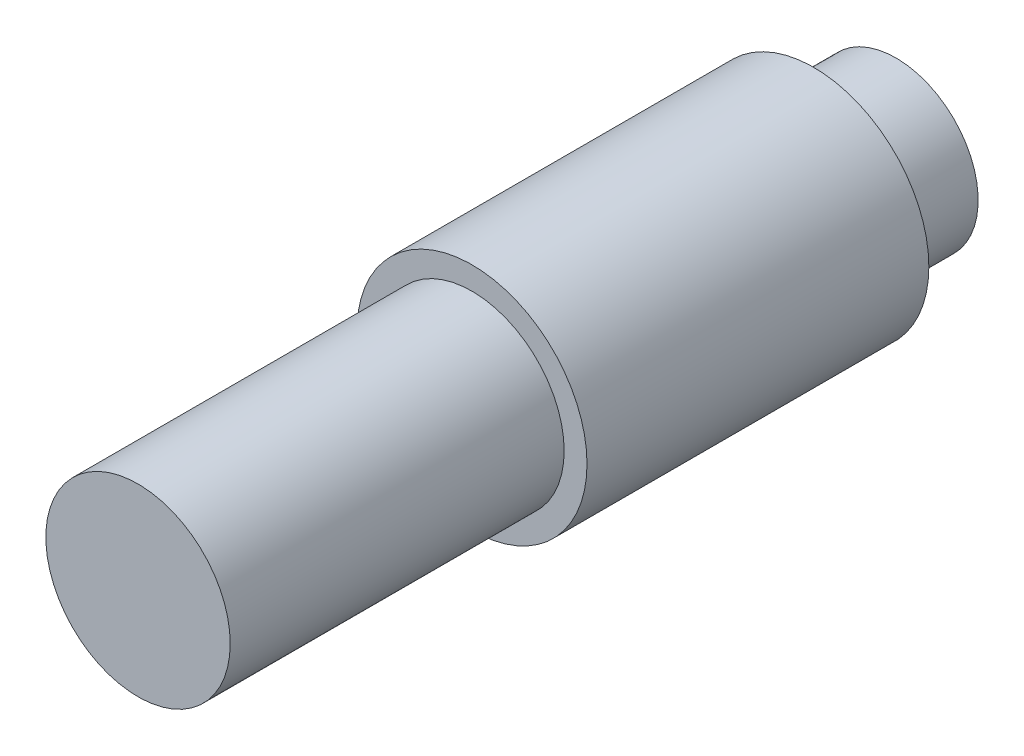
SolidWorks part; units mm, degrees
ref_plane "Front Plane" through (0, 0, 0) normal (0, 0, 1) x (1, 0, 0)
ref_plane "Top Plane" through (0, 0, 0) normal (0, 1, 0) x (1, 0, 0)
ref_plane "Right Plane" through (0, 0, 0) normal (1, 0, 0) x (0, 0, -1)
sketch "Sketch1" plane through (0, 0, 0) normal (0, 0, 1) x (1, 0, 0)
  circle A1 centre (0, 0) radius 23.5 construction
  circle A2 centre (0, 0) radius 17.5
  dimension "D1" = 35
extrude "Boss-Extrude1" add sketch "Sketch1" along normal blind 52
sketch "Sketch2" plane through (0, 0, 52) normal (0, 0, 1) x (1, 0, 0)
  circle A0 centre (0, 0) radius 14.025
extrude "Boss-Extrude2" add sketch "Sketch2" along normal blind 50.8
sketch "Sketch4" plane through (0, 0, 0) normal (0, 0, -1) x (-1, 0, 0)
  circle A0 centre (0, 0) radius 12.5
  dimension "D1" = 25
extrude "Boss-Extrude3" add sketch "Sketch4" along normal blind 12.5
sketch3d "3DSketch1"
  line L0 (0, 0, 102.8) -> (0, 0, -12.5) construction
  line L1 (0, 0, 102.8) -> (0, 0, 52) construction
  line L2 (0, 0, -12.5) -> (0, 0, 0) construction
  line L3 (0, 0, -12.5) -> (0, 0, -83.5963) construction
  line L4 (0, 0, 102.8) -> (0, 0, 197.1641) construction
sketch "Sketch5" plane through (0, 0, -12.5) normal (0, 0, -1) x (-1, 0, 0)
  circle A0 centre (0, 0) radius 164
  dimension "D1" = 328
